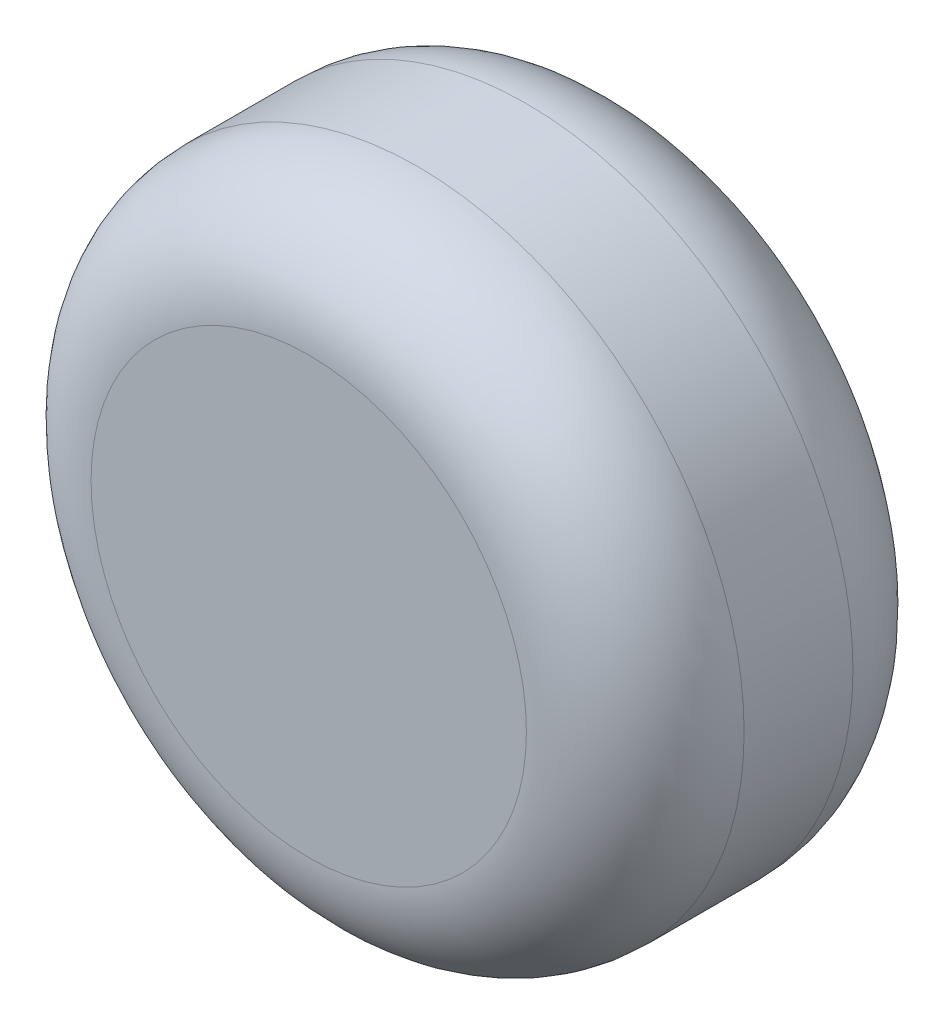
SolidWorks part; units mm, degrees
ref_plane "Plan de face" through (0, 0, 0) normal (0, 0, 1) x (1, 0, 0)
ref_plane "Plan de dessus" through (0, 0, 0) normal (0, 1, 0) x (1, 0, 0)
ref_plane "Plan de droite" through (0, 0, 0) normal (1, 0, 0) x (0, 0, -1)
sketch "Esquisse1" plane through (0, 0, 0) normal (0, 0, 1) x (1, 0, 0)
  circle A0 centre (0, 0) radius 76.2
  dimension "D1" = 152.4
extrude "Boss.-Extru.1" add sketch "Esquisse1" along normal blind 76.2
fillet "Congé1" radius 25.4 2 edges at (76.2, 0, 0) (76.2, 0, 76.2)
